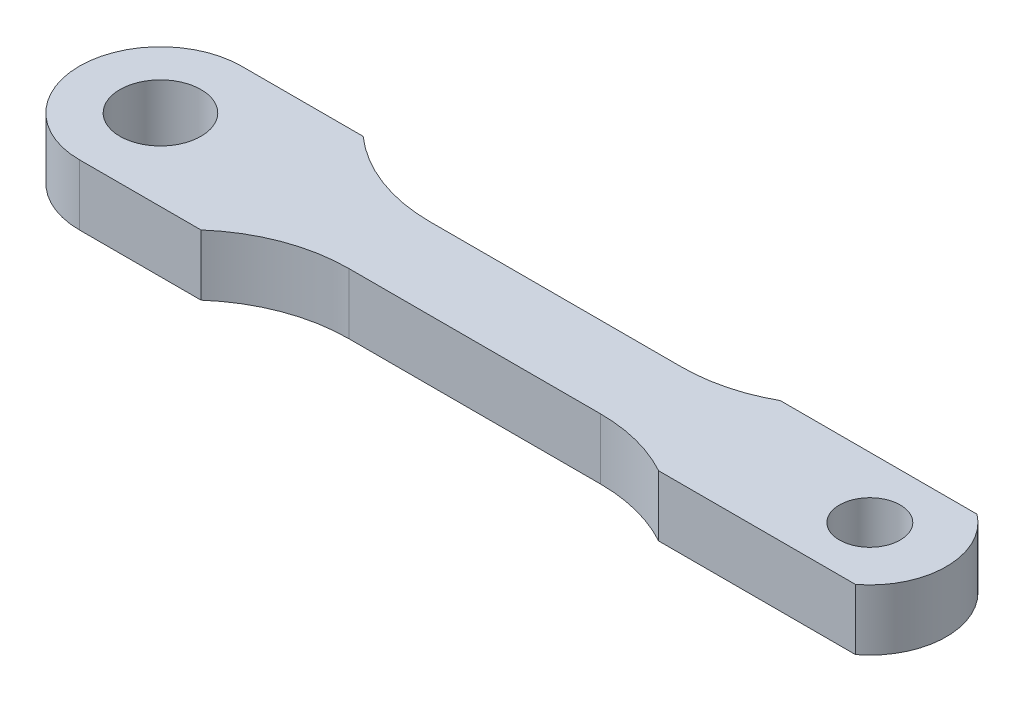
SolidWorks part; units mm, degrees
ref_plane "Front Plane" through (0, 0, 0) normal (0, 0, 1) x (1, 0, 0)
ref_plane "Top Plane" through (0, 0, 0) normal (0, 1, 0) x (1, 0, 0)
ref_plane "Right Plane" through (0, 0, 0) normal (1, 0, 0) x (0, 0, -1)
sketch "Sketch1" plane through (0, 0, 0) normal (0, 1, 0) x (1, 0, 0)
  line L0 (20.0526, 0) -> (-25, 0) construction
  line L1 (0, 7.3158) -> (0, -7.0526) construction
  line L2 (6.2085, -2) -> (-6.2085, -2)
  line L3 (-11.5, -4) -> (-17.5, -4)
  line L4 (10.0815, -3) -> (19.7895, -3)
  line L5 (10.0815, 3) -> (19.7895, 3)
  line L6 (6.2085, 2) -> (-6.2085, 2)
  line L7 (-11.5, 4) -> (-17.5, 4)
  arc A0 (-6.2085, -2) -> (-11.5, -4) centre (-6.2085, -10) ccw
  arc A1 (-17.5, -4) -> (-17.5, 4) centre (-17.5, 0) cw
  arc A2 (19.7895, -3) -> (19.7895, 3) centre (17.5, 0) ccw
  arc A3 (6.2085, -2) -> (10.0815, -3) centre (6.2085, -10) cw
  arc A4 (6.2085, 2) -> (10.0815, 3) centre (6.2085, 10) ccw
  arc A5 (-6.2085, 2) -> (-11.5, 4) centre (-6.2085, 10) cw
  circle A6 centre (-17.5, 0) radius 2
  circle A7 centre (17.5, 0) radius 1.5
  point P18 (0, -2)
  point P26 (0, 0)
  point P27 (0, 0)
  dimension "D4" = 8
  dimension "D5" = 4
  dimension "D6" = 3
  dimension "D1" = 4
  dimension "D2" = 6
  dimension "D3" = 8
  dimension "D7" = 6
  dimension "D8" = 35
extrude "Boss-Extrude1" add sketch "Sketch1" along normal mid plane 3
